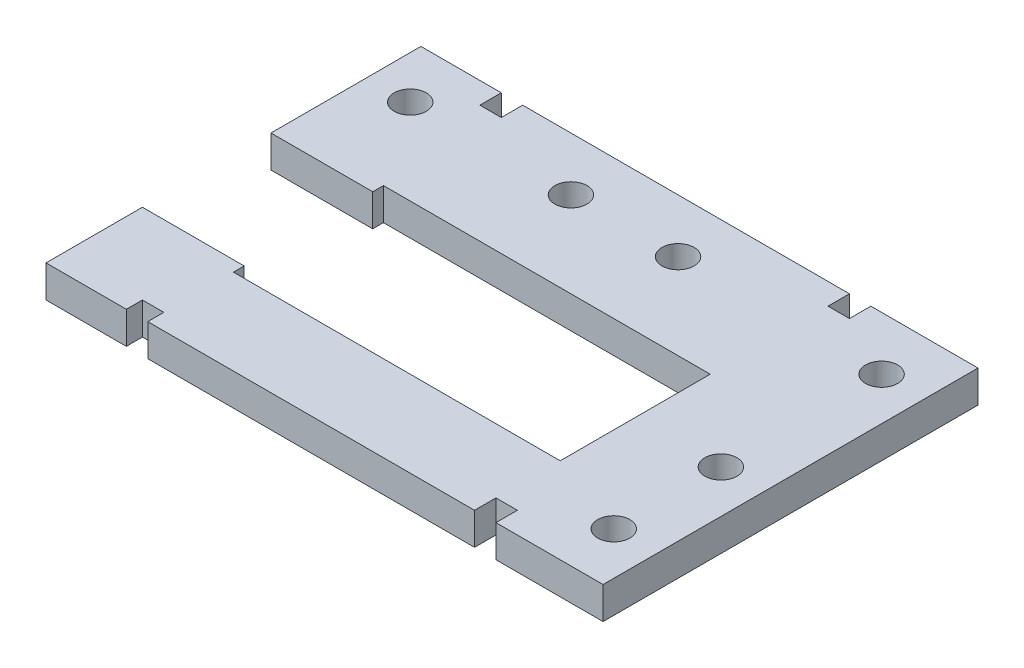
SolidWorks part; units mm, degrees
ref_plane "Front Plane" through (0, 0, 0) normal (0, 0, 1) x (1, 0, 0)
ref_plane "Top Plane" through (0, 0, 0) normal (0, 1, 0) x (1, 0, 0)
ref_plane "Right Plane" through (0, 0, 0) normal (1, 0, 0) x (0, 0, -1)
sketch "Sketch1" plane through (0, 0, 0) normal (0, 1, 0) x (1, 0, 0)
  line L1 (0, 0) -> (52, 0)
  line L2 (0, 0) -> (0, 35)
  line L3 (0, 35) -> (52, 35)
  line L4 (52, 0) -> (52, 35)
  line L5 (40, 22) -> (9.5, 22)
  line L6 (40, 22) -> (40, 8)
  line L7 (40, 8) -> (9.5, 8)
  line L8 (9.5, 22) -> (9.5, 8)
  line L9 (0, 21) -> (9.5, 21)
  line L10 (0, 21) -> (0, 9)
  line L11 (0, 9) -> (9.5, 9)
  line L12 (9.5, 21) -> (9.5, 9)
  line L13 (9.5, 35) -> (7.5, 35)
  line L14 (9.5, 35) -> (9.5, 33)
  line L15 (9.5, 33) -> (7.5, 33)
  line L16 (7.5, 35) -> (7.5, 33)
  line L17 (7.5, 0) -> (9.5, 0)
  line L18 (7.5, 0) -> (7.5, 1.5)
  line L19 (7.5, 1.5) -> (9.5, 1.5)
  line L20 (9.5, 0) -> (9.5, 1.5)
  line L21 (40, 0) -> (42, 0)
  line L22 (40, 0) -> (40, 2)
  line L23 (40, 2) -> (42, 2)
  line L24 (42, 0) -> (42, 2)
  line L25 (40, 35) -> (42, 35)
  line L26 (40, 35) -> (40, 33)
  line L27 (40, 33) -> (42, 33)
  line L28 (42, 35) -> (42, 33)
  circle A0 centre (4, 30) radius 1.5
  circle A1 centre (48, 30) radius 1.5
  circle A2 centre (19, 30) radius 1.5
  circle A3 centre (29, 30) radius 1.5
  circle A4 centre (48, 15) radius 1.5
  circle A5 centre (48, 5) radius 1.5
  dimension "D3" = 44
  dimension "D4" = 5
  dimension "D5" = 3
  dimension "D6" = 3
  dimension "D7" = 5
  dimension "D8" = 4
  dimension "D21" = 15
  dimension "D22" = 10
  dimension "D23" = 3
  dimension "D24" = 3
  dimension "D25" = 5
  dimension "D26" = 5
  dimension "D28" = 3
  dimension "D29" = 3
  dimension "D30" = 4
  dimension "D31" = 4
  dimension "D32" = 10
  dimension "D33" = 15
  dimension "D1" = 52
  dimension "D2" = 35
  dimension "D9" = 30.5
  dimension "D10" = 14
  dimension "D11" = 8
  dimension "D12" = 12
  dimension "D13" = 0
  dimension "D14" = 12
  dimension "D15" = 1
  dimension "D16" = 2
  dimension "D17" = 2
  dimension "D18" = 1.5
  dimension "D19" = 2
  dimension "D20" = 2
  dimension "D27" = 2
  dimension "D34" = 2
  dimension "D35" = 2
  dimension "D36" = 2
  dimension "D37" = 12
  dimension "D38" = 12
  dimension "D39" = 2
extrude "Boss-Extrude1" add sketch "Sketch1" along normal blind 3
